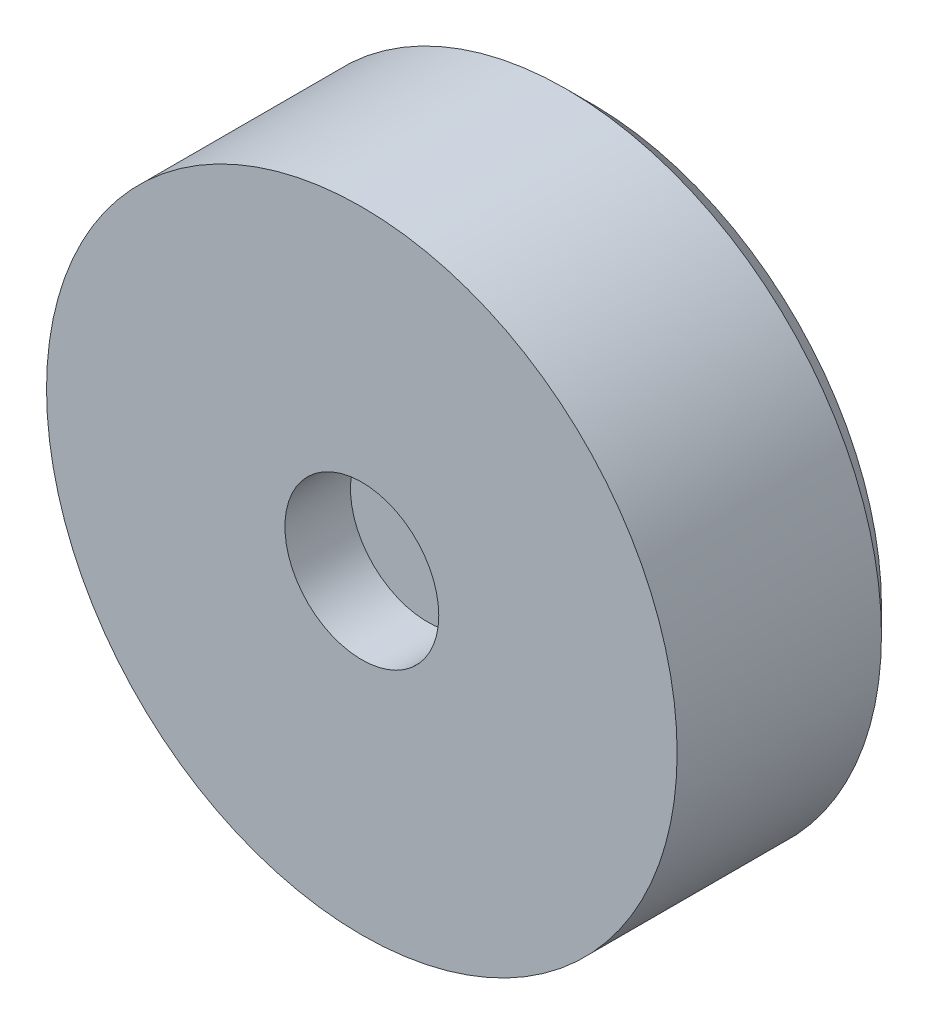
SolidWorks part; units mm, degrees
material "ABS"
ref_plane "Plan de face" through (0, 0, 0) normal (0, 0, 1) x (1, 0, 0)
ref_plane "Plan de dessus" through (0, 0, 0) normal (0, 1, 0) x (1, 0, 0)
ref_plane "Plan de droite" through (0, 0, 0) normal (1, 0, 0) x (0, 0, -1)
sketch "Esquisse1" plane through (0, 0, 0) normal (0, 0, 1) x (1, 0, 0)
  line L1 (-4.9363, -8.55) -> (4.9363, -8.55)
  line L2 (4.9363, -8.55) -> (9.8727, 0)
  line L3 (9.8727, 0) -> (4.9363, 8.55)
  line L4 (4.9363, 8.55) -> (-4.9363, 8.55)
  line L5 (-4.9363, 8.55) -> (-9.8727, 0)
  line L6 (-9.8727, 0) -> (-4.9363, -8.55)
  circle A0 centre (0, 0) radius 8.55 construction
  circle A1 centre (0, 0) radius 12.5
  dimension "D2" = 25
  dimension "D1" = 17.1
extrude "Boss.-Extru.1" add sketch "Esquisse1" along normal blind 2.5
sketch "Esquisse2" plane through (0, 0, 2.5) normal (0, 0, 1) x (1, 0, 0)
  circle A1 centre (0, 0) radius 12.5
  circle A2 centre (0, 0) radius 12.5
  dimension "D1" = 0
extrude "Boss.-Extru.2" add sketch "Esquisse2" along normal blind 4
sketch "Esquisse3" plane through (0, 0, 2.5) normal (0, 0, -1) x (-1, 0, 0)
  circle A0 centre (0, 0) radius 1
  dimension "D1" = 2
extrude "Boss.-Extru.3" add sketch "Esquisse3" along normal blind 2
chamfer "Chanfrein1" distance 1 angle 45 1 edges at (12.5, 0, 0)
sketch "Esquisse4" plane through (0, 0, 6.5) normal (0, 0, 1) x (1, 0, 0)
  circle A0 centre (0, 0) radius 3.05
  circle A1 centre (0, 0) radius 12.5
  dimension "D1" = 25
  dimension "D2" = 6.1
extrude "Boss.-Extru.4" add sketch "Esquisse4" along normal blind 2.6
